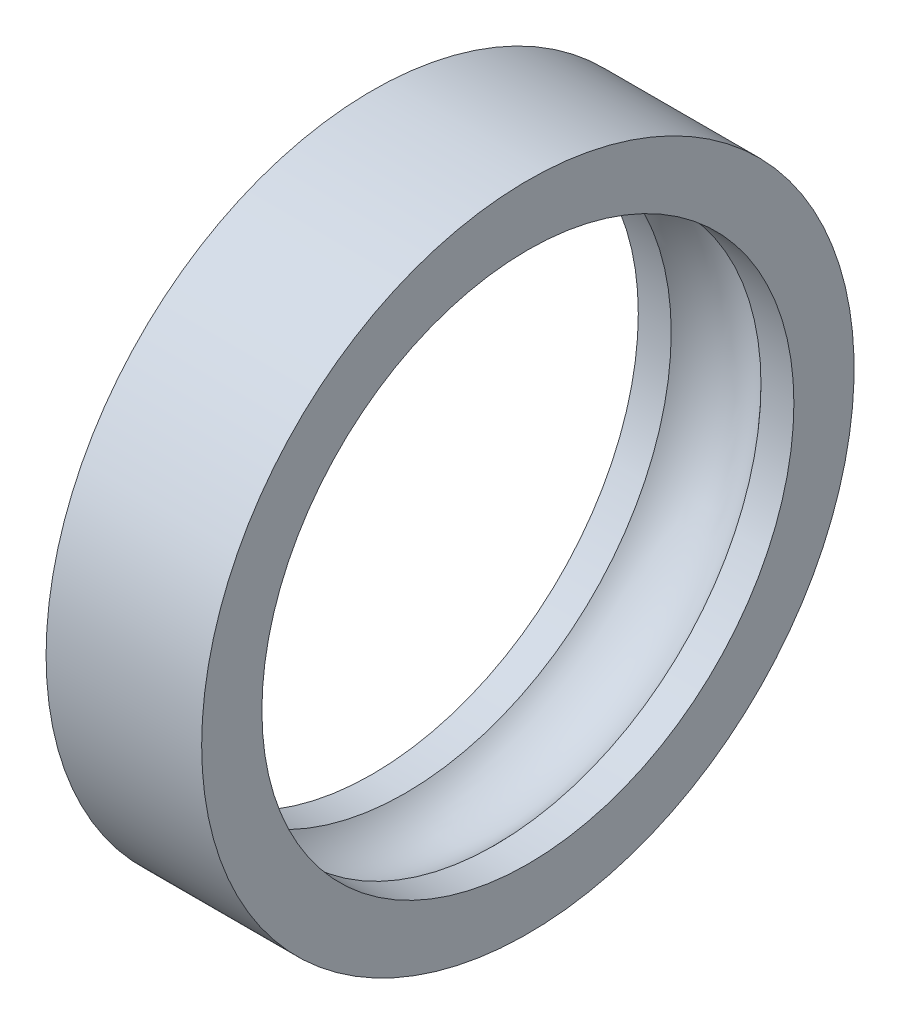
SolidWorks part; units mm, degrees
ref_plane "Front Plane" through (0, 0, 0) normal (0, 0, 1) x (1, 0, 0)
ref_plane "Top Plane" through (0, 0, 0) normal (0, 1, 0) x (1, 0, 0)
ref_plane "Right Plane" through (0, 0, 0) normal (1, 0, 0) x (0, 0, -1)
sketch "Sketch2" plane through (0, 0, 0) normal (0, 0, 1) x (1, 0, 0)
  line L0 (-30.2522, -52.9331) -> (21.2105, -52.9331) construction
  line L1 (-7.2061, 6.0669) -> (-7.2061, -21.9331) construction
  line L2 (-22.7061, 12.0669) -> (8.2939, 12.0669)
  line L3 (-22.7061, 12.0669) -> (-22.7061, 0.0669)
  line L4 (-22.7061, 0.0669) -> (-16.1504, 0.0669)
  line L5 (8.2939, 12.0669) -> (8.2939, 0.0669)
  line L6 (-22.7061, 12.0669) -> (8.2939, 0.0669) construction
  line L7 (-22.7061, 0.0669) -> (8.2939, 12.0669) construction
  line L8 (1.7381, 0.0669) -> (8.2939, 0.0669)
  arc A0 (-16.1504, 0.0669) -> (1.7381, 0.0669) centre (-7.2061, -7.9331) cw
  point P2 (-7.2061, 6.0669)
  dimension "D5" = 12
  dimension "D1" = 31
  dimension "D2" = 65
  dimension "D3" = 53
  dimension "D4" = 8
revolve "Revolve1" add sketch "Sketch2" angle 360 about L0
